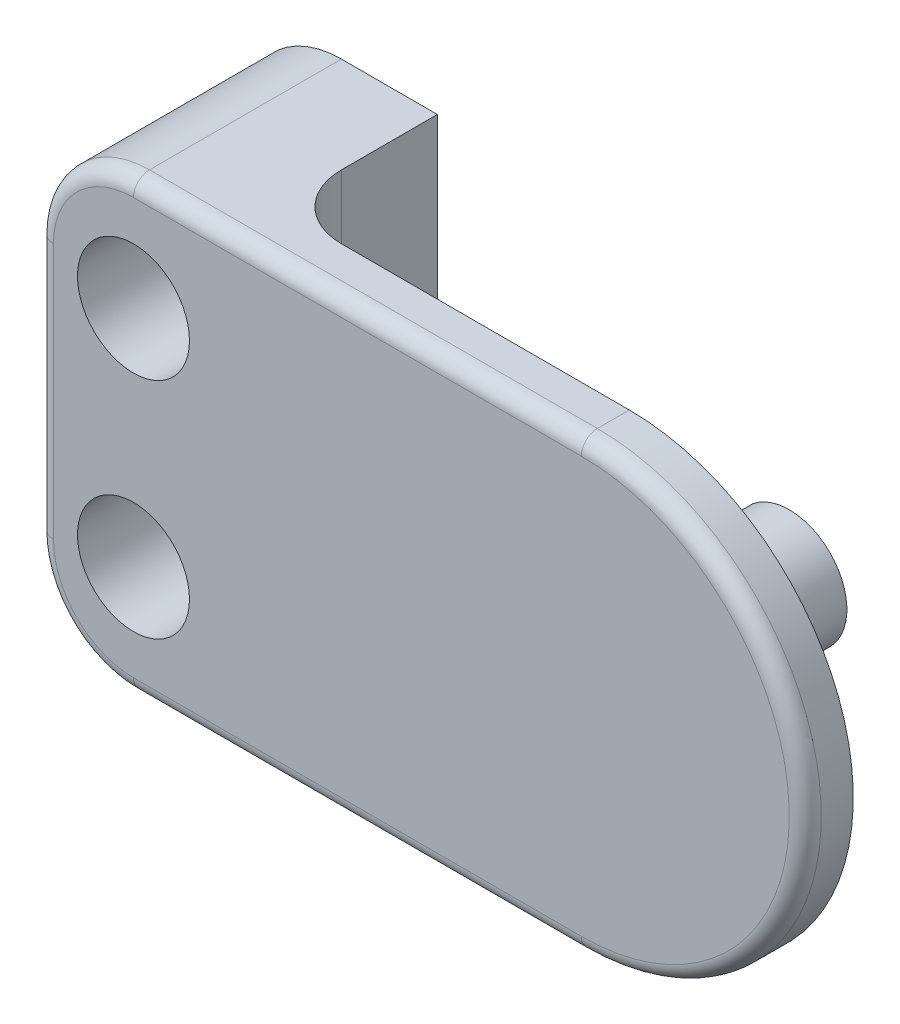
SolidWorks part; units mm, degrees
ref_plane "Front Plane" through (0, 0, 0) normal (0, 0, 1) x (1, 0, 0)
ref_plane "Top Plane" through (0, 0, 0) normal (0, 1, 0) x (1, 0, 0)
ref_plane "Right Plane" through (0, 0, 0) normal (1, 0, 0) x (0, 0, -1)
sketch "Sketch1" plane through (0, 0, 0) normal (0, 0, 1) x (1, 0, 0)
  line L0 (-1.7511, 0) -> (-50001.7511, 0) construction
  line L2 (-17, 7) -> (0, 7)
  line L3 (-17, 7) -> (-17, -7)
  line L4 (-17, -7) -> (0, -7)
  arc A1 (0, 7) -> (0, -7) centre (0, 0) cw
  circle A2 centre (-14, 3.5) radius 1.1
  circle A3 centre (-14, -3.5) radius 1.1
  dimension "D1" = 2.2
  dimension "D2" = 14
  dimension "D3" = 3
  dimension "D4" = 7
  dimension "D5" = 7
extrude "Boss-Extrude1" add sketch "Sketch1" along normal blind 1.5
sketch "Sketch2" plane through (0, 0, 0) normal (0, 0, -1) x (-1, 0, 0)
  circle A0 centre (0, 0) radius 2.5
  dimension "D1" = 5
extrude "Boss-Extrude2" add sketch "Sketch2" along normal blind 1
sketch "Sketch3" plane through (0, 0, -1) normal (0, 0, -1) x (-1, 0, 0)
  line L0 (1.1386, 1.3941) -> (1.1386, -1.3941)
  arc A1 (1.1386, 1.3941) -> (1.1386, -1.3941) centre (0, 0) ccw
  dimension "D1" = 1.8
  dimension "D2" = 1.1386
extrude "Boss-Extrude3" add sketch "Sketch3" along normal blind 4
sketch "Sketch4" plane through (0, 0, 0) normal (0, 0, -1) x (-1, 0, 0)
  line L0 (17, -7) -> (0, -7) construction
  line L1 (17, 7) -> (11, 7)
  line L2 (17, 7) -> (17, -7)
  line L3 (17, -7) -> (11, -7)
  line L4 (11, 7) -> (11, -7)
  circle A0 centre (14, 3.5) radius 1.1
  circle A1 centre (14, -3.5) radius 1.1
  dimension "D1" = 6
extrude "Boss-Extrude4" add sketch "Sketch4" along normal blind 5
fillet "Fillet4" radius 3 2 edges at (-17, 7, -1.75) (-17, -7, -1.75)
fillet "Fillet1" radius 0.5 6 edges at (-7, -7, 1.5) (7, 0, 1.5) (-7, 7, 1.5) (-16.1213, -6.1213, 1.5) (-17, 0, 1.5) (-16.1213, 6.1213, 1.5)
sketch "Sketch5" plane through (0, 0, 1.5) normal (0, 0, 1) x (1, 0, 0)
  circle A0 centre (-14, 3.5) radius 1.75
  circle A1 centre (-14, -3.5) radius 1.75
  dimension "D1" = 3.5
extrude "Cut-Extrude1" cut sketch "Sketch5" against normal blind 4
fillet "Fillet3" radius 2 1 edges at (-11, 0, 0)
